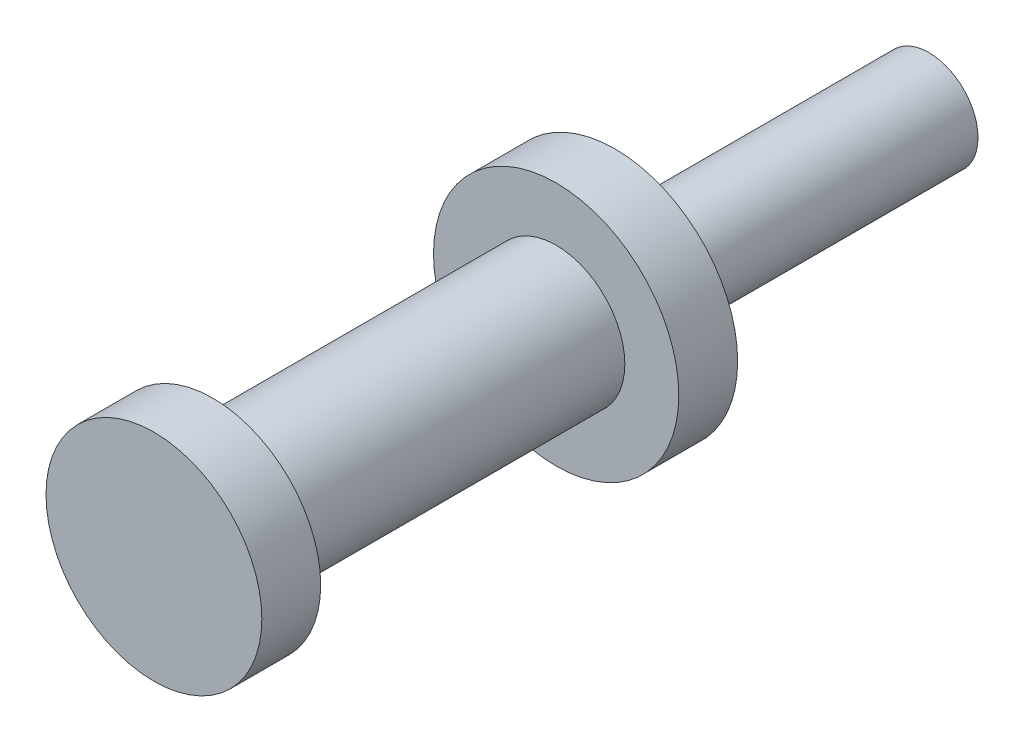
SolidWorks part; units mm, degrees
ref_plane "Front Plane" through (0, 0, 0) normal (0, 0, 1) x (1, 0, 0)
ref_plane "Top Plane" through (0, 0, 0) normal (0, 1, 0) x (1, 0, 0)
ref_plane "Right Plane" through (0, 0, 0) normal (1, 0, 0) x (0, 0, -1)
sketch "Sketch1" plane through (0, 0, 0) normal (1, 0, 0) x (0, 0, -1)
  line L0 (0, 0) -> (0.6, 0)
  line L1 (0, 0) -> (0, -1.1)
  line L2 (0, -1.1) -> (0.6, -1.1) construction
  line L3 (0.6, -1.1) -> (0.6, -0.4) construction
  line L4 (0.6, 0) -> (0.6, -0.4)
  line L5 (0.6, -0.4) -> (4.1, -0.4)
  line L6 (0.6, -1.1) -> (4.1, -1.1) construction
  line L7 (4.1, -1.1) -> (4.1, 0.15) construction
  line L8 (4.1, -0.4) -> (4.1, 0.15)
  line L9 (4.1, 0.15) -> (4.7, 0.15)
  line L10 (4.1, -1.1) -> (4.7, -1.1) construction
  line L11 (4.7, -1.1) -> (4.7, -0.6) construction
  line L12 (4.7, 0.15) -> (4.7, -0.6)
  line L13 (4.7, -0.6) -> (7.9, -0.6)
  line L14 (7.9, -0.6) -> (7.9, -1.1)
  line L15 (7.9, -1.1) -> (4.7, -1.1) construction
  line L16 (0, -1.1) -> (7.9, -1.1)
  dimension "D1" = 0.6
  dimension "D2" = 1.1
  dimension "D3" = 0.7
  dimension "D4" = 3.5
  dimension "D5" = 1.25
  dimension "D6" = 0.6
  dimension "D7" = 0.5
  dimension "D8" = 3.2
revolve "Revolve1" add sketch "Sketch1" angle 360 about L16
